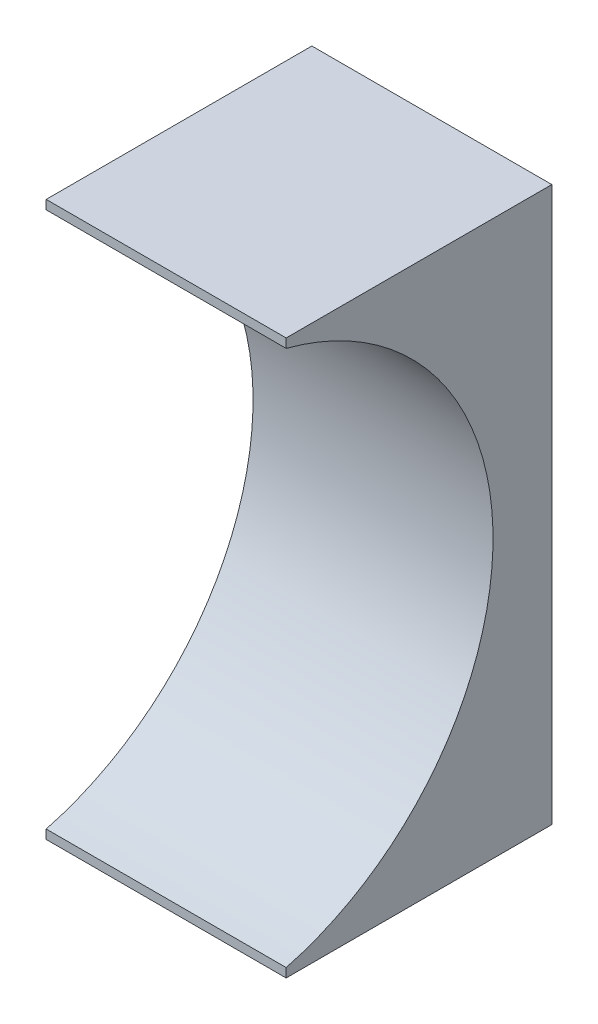
SolidWorks part; units mm, degrees
ref_plane "Alzado" through (0, 0, 0) normal (0, 0, 1) x (1, 0, 0)
ref_plane "Planta" through (0, 0, 0) normal (0, 1, 0) x (1, 0, 0)
ref_plane "Vista lateral" through (0, 0, 0) normal (1, 0, 0) x (0, 0, -1)
sketch "Croquis4" plane through (0, 0, 0) normal (1, 0, 0) x (0, 0, -1)
  line L0 (0, -23.1) -> (0, 23.1) construction
  line L1 (0, 23.1) -> (28, 23.1)
  line L2 (0, -23.1) -> (28, -23.1)
  line L3 (28, -23.1) -> (28, 23.1)
  arc A0 (0, -23.1) -> (0, 23.1) centre (0, 0) ccw
  dimension "D1" = 23.1
  dimension "D2" = 28
extrude "Saliente-Extruir2" add sketch "Croquis4" along normal blind 20
ref_plane "Plano1" through (20, 0, 0) normal (1, 0, 0) x (0, 0, -1)
sketch "Croquis5" plane through (20, 0, 0) normal (1, 0, 0) x (0, 0, -1)
  line L0 (5.857, 23.1) -> (5.857, -23.1)
  line L1 (28, 23.1) -> (0, 23.1) construction
  line L2 (0, -23.1) -> (28, -23.1) construction
  line L3 (5.857, -23.1) -> (28, -23.1)
  line L4 (28, -23.1) -> (28, 23.1)
  line L5 (28, -23.1) -> (28, 23.1) construction
  line L6 (28, 23.1) -> (5.857, 23.1)
extrude "Cortar-Extruir1" cut sketch "Croquis5" against normal through all flip side to cut
